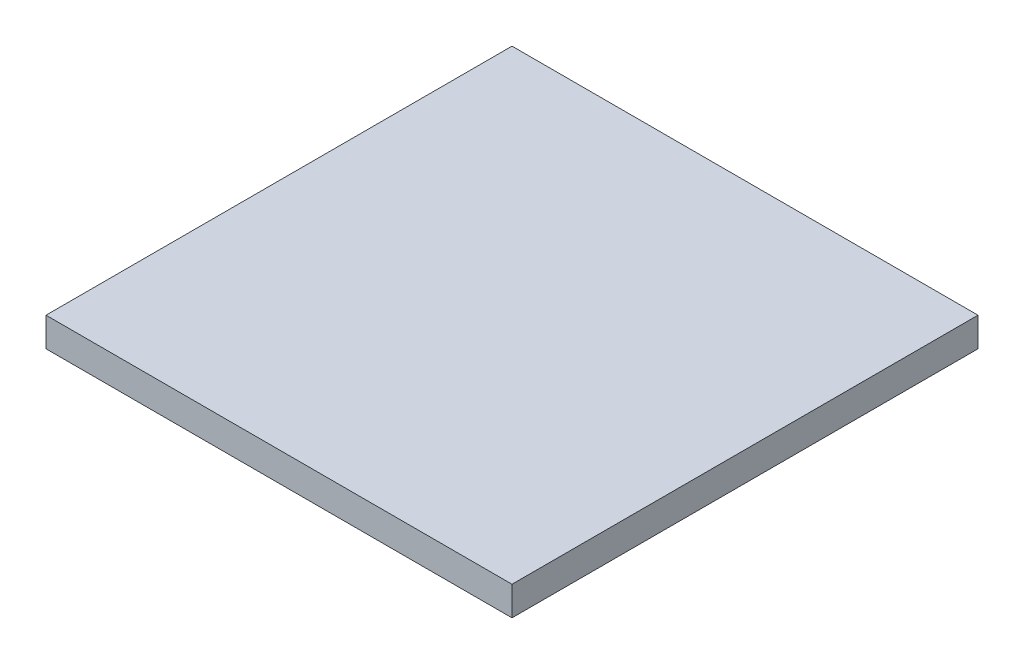
SolidWorks part; units mm, degrees
ref_plane "Спереди" through (0, 0, 0) normal (0, 0, 1) x (1, 0, 0)
ref_plane "Сверху" through (0, 0, 0) normal (0, 1, 0) x (1, 0, 0)
ref_plane "Справа" through (0, 0, 0) normal (1, 0, 0) x (0, 0, -1)
sketch "Эскиз1" plane through (0, 0, 0) normal (0, 1, 0) x (1, 0, 0)
  line L1 (80, -80) -> (-80, -80)
  line L2 (80, -80) -> (80, 80)
  line L3 (80, 80) -> (-80, 80)
  line L4 (-80, -80) -> (-80, 80)
  line L5 (0, 80) -> (0, -80) construction
  line L6 (80, 0) -> (-80, 0) construction
  point P0 (0, 0)
  dimension "D1" = 160
extrude "Бобышка-Вытянуть1" add sketch "Эскиз1" against normal blind 10
